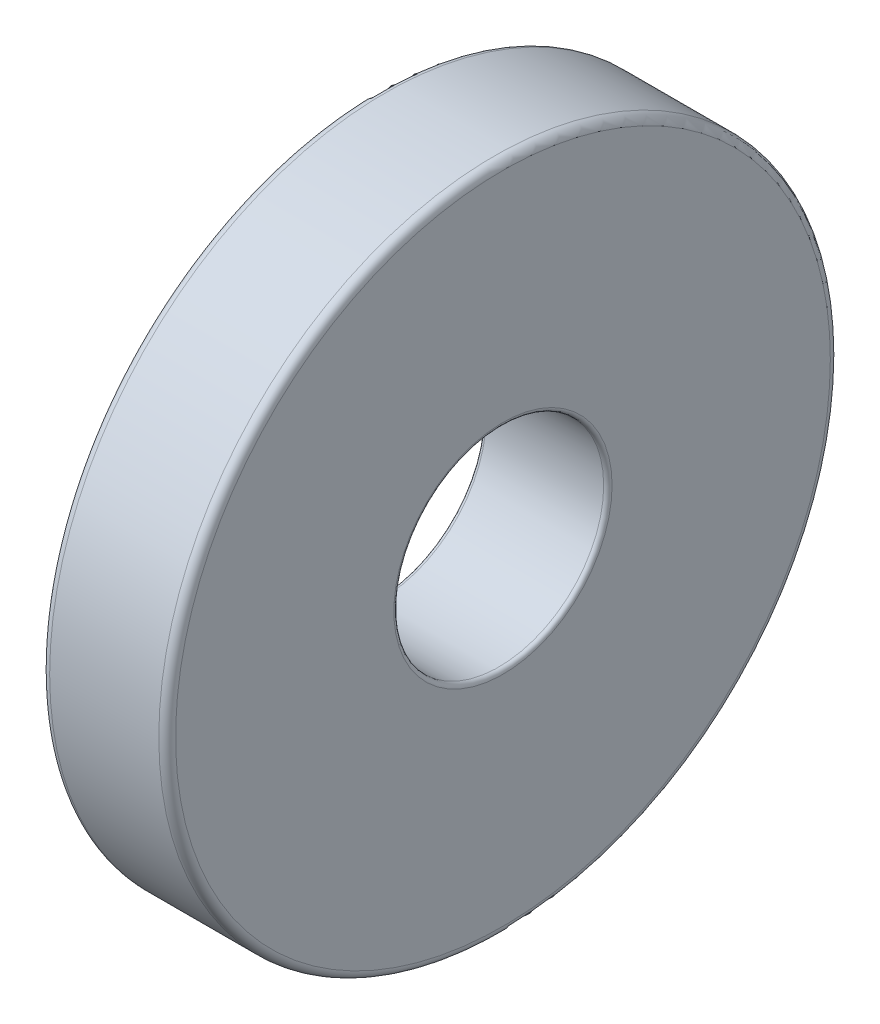
SolidWorks part; units mm, degrees
ref_plane "Front Plane" through (0, 0, 0) normal (0, 0, 1) x (1, 0, 0)
ref_plane "Top Plane" through (0, 0, 0) normal (0, 1, 0) x (1, 0, 0)
ref_plane "Right Plane" through (0, 0, 0) normal (1, 0, 0) x (0, 0, -1)
sketch "Sketch1" plane through (0, 0, 0) normal (1, 0, 0) x (0, 0, -1)
  circle A0 centre (0, 0) radius 80
  circle A1 centre (0, 0) radius 25
  dimension "D1" = 160
  dimension "D2" = 50
extrude "Boss-Extrude1" add sketch "Sketch1" along normal blind 30
fillet "Fillet2" radius 2 2 edges at (30, 0, -80) (0, 0, -80)
fillet "Fillet3" radius 1 2 edges at (30, 0, -25) (0, 0, -25)
